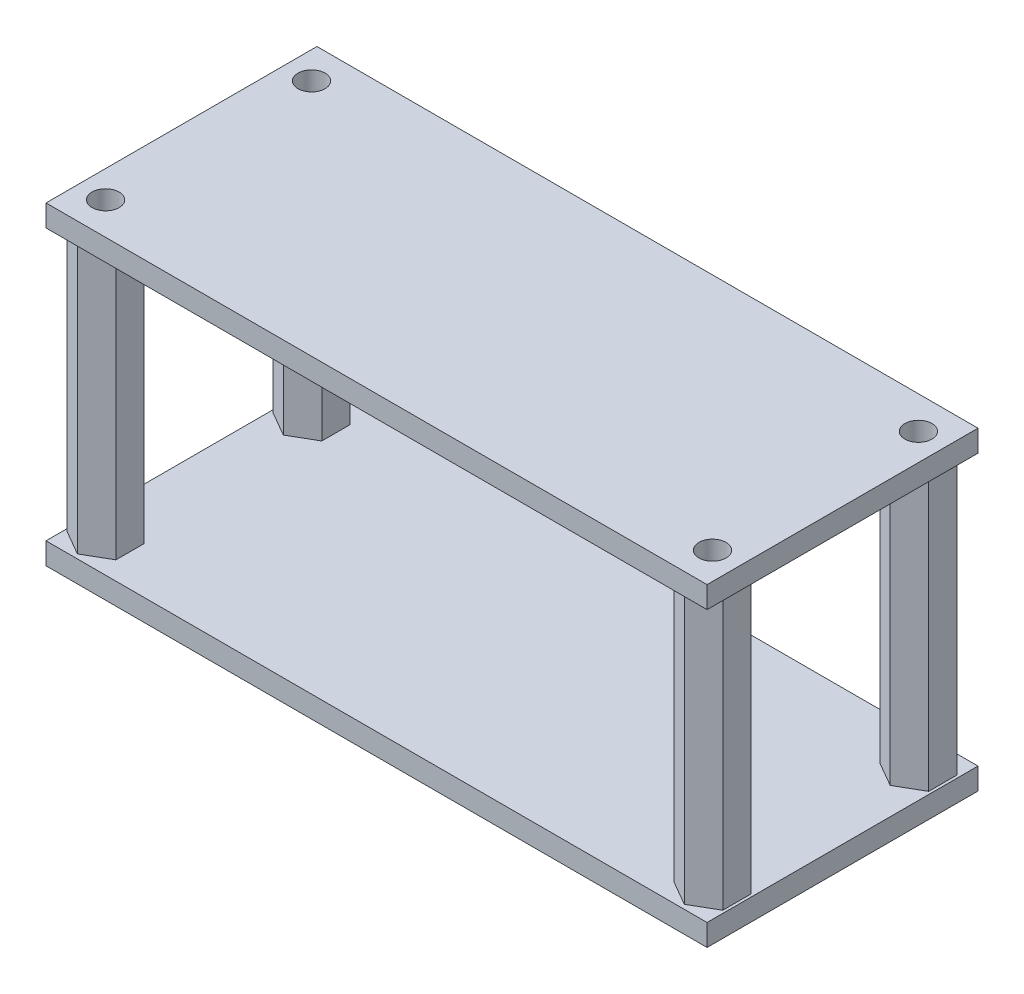
SolidWorks part; units mm, degrees
ref_plane "前视基准面" through (0, 0, 0) normal (0, 0, 1) x (1, 0, 0)
ref_plane "上视基准面" through (0, 0, 0) normal (0, 1, 0) x (1, 0, 0)
ref_plane "右视基准面" through (0, 0, 0) normal (1, 0, 0) x (0, 0, -1)
sketch "草图1" plane through (0, 0, 0) normal (0, 1, 0) x (1, 0, 0)
  line L1 (-30.5, -12.5) -> (30.5, -12.5)
  line L2 (-30.5, -12.5) -> (-30.5, 12.5)
  line L3 (-30.5, 12.5) -> (30.5, 12.5)
  line L4 (30.5, -12.5) -> (30.5, 12.5)
  line L5 (-30.5, -12.5) -> (30.5, 12.5) construction
  line L6 (-30.5, 12.5) -> (30.5, -12.5) construction
  point P0 (0, 0)
  dimension "D1" = 61
  dimension "D2" = 25
extrude "凸台-拉伸1" add sketch "草图1" along normal blind 2
sketch "草图2" plane through (0, 2, 0) normal (0, 1, 0) x (1, 0, 0)
  line L1 (-28, -9.5) -> (28, -9.5) construction
  line L2 (-28, -9.5) -> (-28, 9.5) construction
  line L3 (-28, 9.5) -> (28, 9.5) construction
  line L4 (28, -9.5) -> (28, 9.5) construction
  line L5 (-28, -9.5) -> (28, 9.5) construction
  line L6 (-28, 9.5) -> (28, -9.5) construction
  circle A0 centre (-28, 9.5) radius 1.25
  circle A1 centre (-28, -9.5) radius 1.25
  circle A2 centre (28, 9.5) radius 1.25
  circle A3 centre (28, -9.5) radius 1.25
  point P0 (0, 0)
  dimension "D3" = 2.5
  dimension "D1" = 56
  dimension "D2" = 19
extrude "切除-拉伸1" cut sketch "草图2" against normal blind 52
sketch "草图3" plane through (0, 2, 0) normal (0, 1, 0) x (1, 0, 0)
  line L0 (-30.5, 0) -> (30.5, 0) construction
  line L1 (-25.75, 10.799) -> (-28, 12.0981)
  line L2 (-28, 12.0981) -> (-30.25, 10.799)
  line L3 (-30.25, 10.799) -> (-30.25, 8.201)
  line L4 (-30.25, 8.201) -> (-28, 6.9019)
  line L5 (-28, 6.9019) -> (-25.75, 8.201)
  line L6 (-25.75, 8.201) -> (-25.75, 10.799)
  line L7 (-30.5, 12.5) -> (-30.5, -12.5) construction
  line L8 (30.5, -12.5) -> (30.5, 12.5) construction
  line L9 (0, 12.5) -> (0, -12.5) construction
  line L10 (30.5, 12.5) -> (-30.5, 12.5) construction
  line L11 (-30.5, -12.5) -> (30.5, -12.5) construction
  line L12 (25.75, 8.201) -> (25.75, 10.799)
  line L13 (28, 6.9019) -> (25.75, 8.201)
  line L14 (30.25, 8.201) -> (28, 6.9019)
  line L15 (30.25, 10.799) -> (30.25, 8.201)
  line L16 (28, 12.0981) -> (30.25, 10.799)
  line L17 (25.75, 10.799) -> (28, 12.0981)
  line L18 (25.75, -10.799) -> (28, -12.0981)
  line L19 (28, -12.0981) -> (30.25, -10.799)
  line L20 (30.25, -10.799) -> (30.25, -8.201)
  line L21 (30.25, -8.201) -> (28, -6.9019)
  line L22 (28, -6.9019) -> (25.75, -8.201)
  line L23 (25.75, -8.201) -> (25.75, -10.799)
  line L24 (-25.75, -8.201) -> (-25.75, -10.799)
  line L25 (-28, -6.9019) -> (-25.75, -8.201)
  line L26 (-30.25, -8.201) -> (-28, -6.9019)
  line L27 (-30.25, -10.799) -> (-30.25, -8.201)
  line L28 (-28, -12.0981) -> (-30.25, -10.799)
  line L29 (-25.75, -10.799) -> (-28, -12.0981)
  circle A0 centre (-28, 9.5) radius 2.25 construction
  circle A1 centre (-28, 9.5) radius 1.25 construction
  circle A2 centre (-28, 9.5) radius 1.25
  circle A3 centre (28, 9.5) radius 2.25 construction
  circle A4 centre (28, 9.5) radius 1.25
  circle A5 centre (28, -9.5) radius 2.25 construction
  circle A6 centre (-28, -9.5) radius 2.25 construction
  circle A7 centre (28, -9.5) radius 1.25
  circle A8 centre (-28, -9.5) radius 1.25
  dimension "D1" = 4.5
extrude "凸台-拉伸2" add sketch "草图3" along normal blind 25 separate body
move or copy body "实体-移动/复制1" bodies to move or copy 107 copy yes number of copies 1 translate (0, 27, 0)
